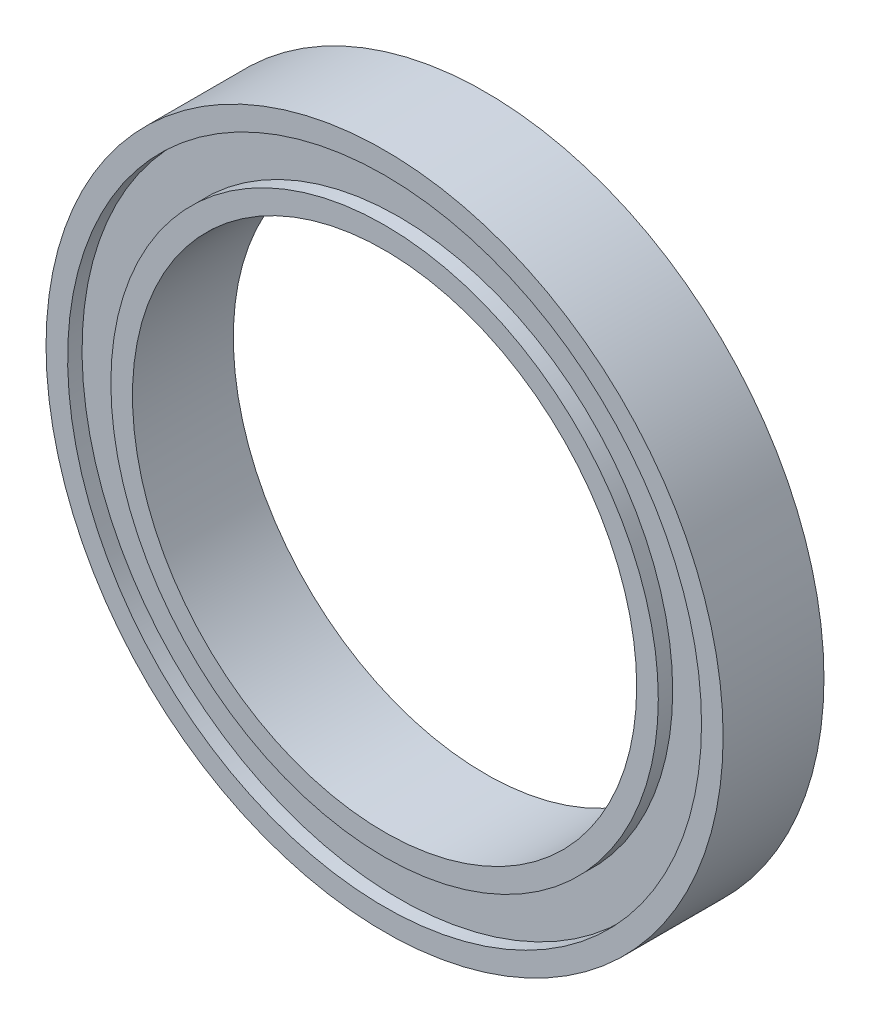
SolidWorks part; units mm, degrees
ref_plane "Front Plane" through (0, 0, 0) normal (1, 0, 0) x (0, 1, 0)
ref_plane "Top Plane" through (0, 0, 0) normal (0, 0, 1) x (0, 1, 0)
ref_plane "Right Plane" through (0, 0, 0) normal (0, 1, 0) x (-1, 0, 0)
sketch "Sketch1" plane through (0, 0, 0) normal (0, 0, 1) x (0, 1, 0)
  circle A0 centre (0, 0) radius 23.5
  dimension "D1" = 47
extrude "Boss-Extrude1" add sketch "Sketch1" along normal blind 7
sketch "Sketch2" plane through (0, 0, 0) normal (0, 0, 1) x (0, 1, 0)
  circle A0 centre (0, 0) radius 17.5
  dimension "D1" = 35
extrude "Cut-Extrude1" cut sketch "Sketch2" along normal through all
sketch "Sketch3" plane through (0, 0, 0) normal (0, 0, -1) x (1, 0, 0)
  circle A0 centre (0, 0) radius 20.5
  dimension "D1" = 41
extrude "Cut-Extrude-Thin1" cut sketch "Sketch3" against normal through all thin thin type mid plane wall 3
sketch "Sketch4" plane through (0, 0, 0) normal (0, 0, 1) x (0, 1, 0)
  circle A0 centre (0, 0) radius 20.5
  dimension "D1" = 41
extrude "Extrude-Thin1" add sketch "Sketch4" along normal blind 5 from offset 1 thin thin type mid plane wall 3
